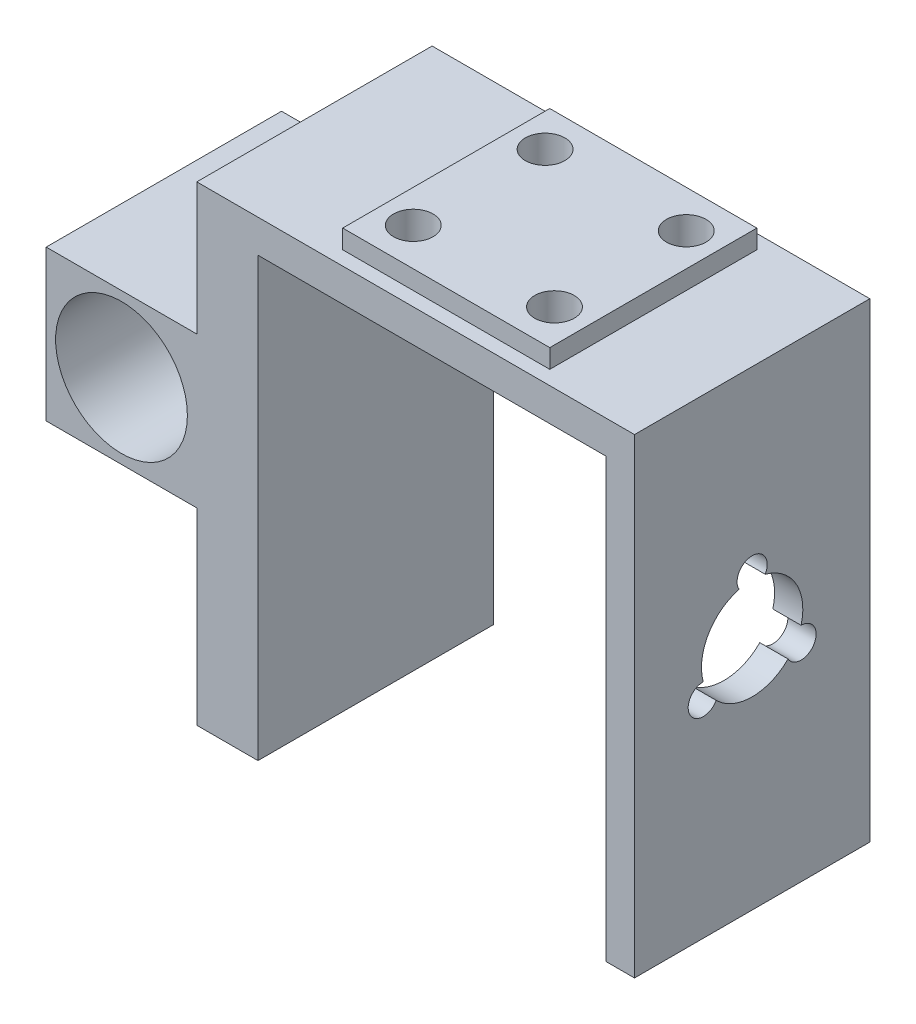
SolidWorks part; units mm, degrees
ref_plane "前视基准面" through (0, 0, 0) normal (0, 0, 1) x (1, 0, 0)
ref_plane "上视基准面" through (0, 0, 0) normal (0, 1, 0) x (1, 0, 0)
ref_plane "右视基准面" through (0, 0, 0) normal (1, 0, 0) x (0, 0, -1)
other "Configuration Table"
sketch "草图1" plane through (0, 0, 0) normal (0, 0, 1) x (1, 0, 0)
  line L1 (-25, 25) -> (25, 25)
  line L2 (-25, 25) -> (-25, -25)
  line L3 (-25, -25) -> (25, -25)
  line L4 (25, 25) -> (25, -25)
  line L5 (-25, 25) -> (25, -25) construction
  line L6 (-25, -25) -> (25, 25) construction
  point P0 (0, 0)
  dimension "D1" = 50
extrude "凸台-拉伸1" add sketch "草图1" along normal blind 25
sketch "草图3" plane through (0, 0, 25) normal (0, 0, 1) x (1, 0, 0)
  line L0 (-18.5, -15.5) -> (-18.5, -25)
  line L1 (-18.5, 21.5) -> (18.5, 21.5)
  line L2 (-18.5, 21.5) -> (-18.5, -15.5)
  line L4 (18.5, 21.5) -> (18.5, -15.5)
  line L5 (-18.5, 21.5) -> (18.5, -15.5) construction
  line L6 (-18.5, -15.5) -> (18.5, 21.5) construction
  line L7 (-25, -25) -> (25, -25) construction
  line L8 (-18.5, -25) -> (18.5, -25)
  line L9 (18.5, -25) -> (18.5, -15.5)
  point P0 (0, 3)
  dimension "D1" = 37
extrude "切除-拉伸1" cut sketch "草图3" against normal blind 12
sketch "草图5" plane through (0, 0, 25) normal (0, 0, 1) x (1, 0, 0)
  line L1 (-41, 11) -> (-25, 11)
  line L2 (-41, 11) -> (-41, -5)
  line L3 (-41, -5) -> (-25, -5)
  line L4 (-25, 11) -> (-25, -5)
  line L5 (-41, 11) -> (-25, -5) construction
  line L6 (-41, -5) -> (-25, 11) construction
  point P0 (-33, 3)
  dimension "D1" = 16
extrude "凸台-拉伸2" add sketch "草图5" against normal blind 25
sketch "草图6" plane through (0, 0, 25) normal (0, 0, 1) x (1, 0, 0)
  circle A0 centre (-33, 3) radius 7
extrude "切除-拉伸3" cut sketch "草图6" against normal blind 25
sketch "草图7" plane through (-41, 0, 0) normal (-1, 0, 0) x (0, 0, 1)
  circle A0 centre (12.5, 3) radius 2.1
extrude "切除-拉伸4" cut sketch "草图7" against normal blind 7
sketch "草图10" plane through (0, 11, 0) normal (0, 1, 0) x (1, 0, 0)
  circle A0 centre (-33, -12.5) radius 2.1
extrude "切除-拉伸5" cut sketch "草图10" against normal blind 26
sketch "草图15" plane through (0, 25, 0) normal (0, 1, 0) x (1, 0, 0)
  line L1 (-11, -1.5) -> (11, -1.5)
  line L2 (-11, -1.5) -> (-11, -23.5)
  line L3 (-11, -23.5) -> (11, -23.5)
  line L4 (11, -1.5) -> (11, -23.5)
  line L5 (-11, -1.5) -> (11, -23.5) construction
  line L6 (-11, -23.5) -> (11, -1.5) construction
  point P0 (0, -12.5)
  point P5 (0, 0)
  point P6 (0, 0)
  dimension "D1" = 22
extrude "凸台-拉伸3" add sketch "草图15" along normal blind 2
sketch "草图16" plane through (0, 27, 0) normal (0, 1, 0) x (1, 0, 0)
  line L1 (-7.5, -5.5) -> (7.5, -5.5)
  line L2 (-7.5, -5.5) -> (-7.5, -19.5)
  line L3 (-7.5, -19.5) -> (7.5, -19.5)
  line L4 (7.5, -5.5) -> (7.5, -19.5)
  line L5 (-7.5, -5.5) -> (7.5, -19.5) construction
  line L6 (-7.5, -19.5) -> (7.5, -5.5) construction
  circle A0 centre (-7.5, -5.5) radius 2.1
  circle A1 centre (7.5, -5.5) radius 2.1
  circle A2 centre (-7.5, -19.5) radius 2.1
  circle A3 centre (7.5, -19.5) radius 2.1
  point P0 (0, -12.5)
  dimension "D1" = 14
  dimension "D2" = 15
extrude "切除-拉伸6" cut sketch "草图16" against normal blind 4 contours A3 | A1 | A2 | A0
sketch "草图23" plane through (25, 0, 0) normal (1, 0, 0) x (0, 0, -1)
  circle A0 centre (-12.5, 0) radius 6
  circle A1 centre (-12.5, 6) radius 1.6
  circle A2 centre (-7.3038, -3) radius 1.6
  circle A3 centre (-17.6962, -3) radius 1.6
  dimension "D1" = 3
sketch "草图24" plane through (0, 0, 13) normal (0, 0, 1) x (1, 0, 0)
  line L1 (-18.5, 11.7225) -> (18.5, 11.7225)
  line L2 (-18.5, 11.7225) -> (-18.5, -25.858)
  line L3 (-18.5, -25.858) -> (18.5, -25.858)
  line L4 (18.5, 11.7225) -> (18.5, -25.858)
  line L7 (-18.5, 21.5) -> (-18.5, -25) construction
  line L8 (18.5, -25) -> (18.5, 21.5) construction
  line L9 (18.5, -25) -> (18.5, 21.5) construction
  dimension "D1" = 37.5805
  dimension "D2" = 37
extrude "切除-拉伸7" cut sketch "草图24" against normal blind 25 contours L1 L4 L3 L2
extrude "切除-拉伸8" cut sketch "草图23" against normal blind 11 contours A2 | A3 | A1
sketch "草图25" plane through (25, 0, 0) normal (1, 0, 0) x (0, 0, -1)
  circle A0 centre (-12.5, 0) radius 5.3849
extrude "切除-拉伸9" cut sketch "草图25" against normal blind 9
sketch "草图27" plane through (0, 0, 25) normal (0, 0, 1) x (1, 0, 0)
  line L1 (25, 25) -> (21.5, 25)
  line L2 (25, 25) -> (25, -25)
  line L3 (25, -25) -> (21.5, -25)
  line L4 (21.5, 25) -> (21.5, -25)
  line L5 (18.5, -25) -> (25, -25) construction
  dimension "D1" = 50
  dimension "D2" = 3.5
extrude "切除-拉伸10" cut sketch "草图27" against normal blind 25
